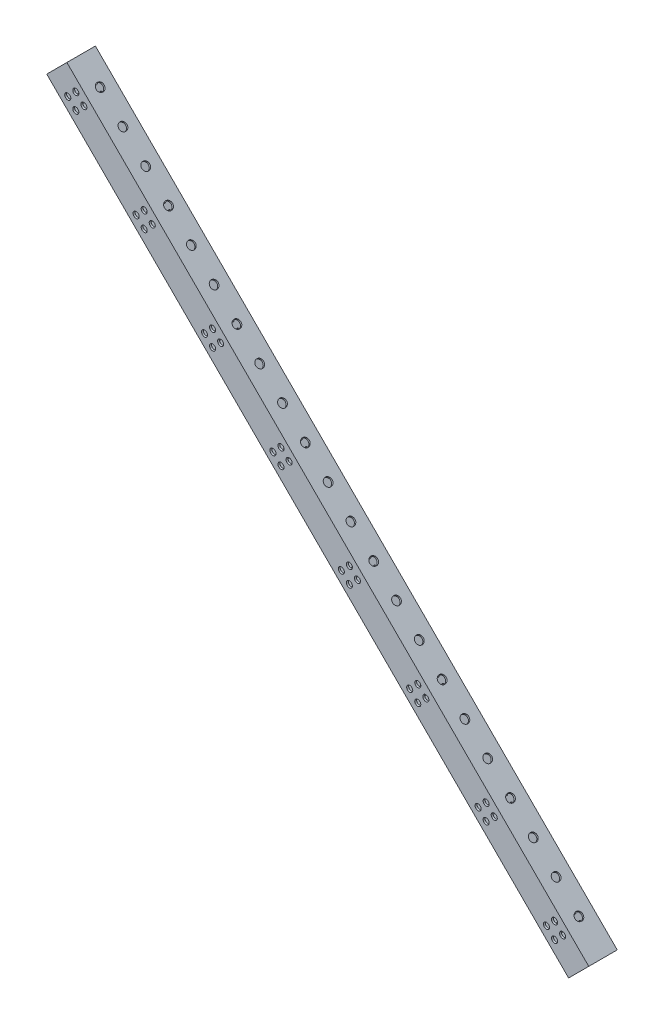
SolidWorks part; units mm, degrees
ref_plane "前视基准面" through (0, 0, 0) normal (0, 0, 1) x (1, 0, 0)
ref_plane "上视基准面" through (0, 0, 0) normal (0, 1, 0) x (1, 0, 0)
ref_plane "右视基准面" through (0, 0, 0) normal (1, 0, 0) x (0, 0, -1)
other "Configuration Table"
sketch "草图1" plane through (0, 0, 0) normal (0, 0, 1) x (1, 0, 0)
  line L0 (0, 560) -> (0, 0) construction
  line L1 (0, 0) -> (560, 0) construction
  line L2 (0, 0) -> (49.7921, 0) construction
  line L3 (5.3033, 565.3033) -> (-5.3033, 554.6967)
  line L8 (-5.3033, 554.6967) -> (554.6967, -5.3033)
  line L9 (554.6967, -5.3033) -> (565.3033, 5.3033)
  line L10 (565.3033, 5.3033) -> (5.3033, 565.3033)
  point P5 (0, 0)
  dimension "D1" = 90
  dimension "D2" = 560
  dimension "D3" = 560
  dimension "D4" = 15
extrude "凸台-拉伸1" add sketch "草图1" along normal blind 15
sketch "草图3" plane through (-280, 280, 0) normal (-0.7071, 0.7071, 0) x (0, 0, 1)
  line L0 (15, 403.4798) -> (0, 403.4798) construction
  line L1 (1, 389.4798) -> (14, 389.4798)
  line L2 (1, 389.4798) -> (1, 402.4798)
  line L3 (1, 402.4798) -> (14, 402.4798)
  line L4 (14, 389.4798) -> (14, 402.4798)
  line L5 (0, 403.4798) -> (0, 388.4798) construction
  dimension "D1" = 1
  dimension "D2" = 1
  dimension "D3" = 13
extrude "切除-拉伸2" cut sketch "草图3" against normal up to surface (791.9596 mm away) up to face at (560, 0, 7.5)
sketch "草图4" plane through (0, 0, 15) normal (0, 0, 1) x (1, 0, 0)
  line L0 (0, 560) -> (9.2347, 550.7653) construction
  line L2 (5.3033, 565.3033) -> (-5.3033, 554.6967) construction
  line L3 (-5.3033, 554.6967) -> (554.6967, -5.3033) construction
  line L4 (0, 560) -> (0, 540) construction
  line L5 (0, 540) -> (20, 540) construction
  circle A0 centre (5.7574, 550) radius 1.6
  circle A1 centre (10, 554.2426) radius 1.6
  circle A2 centre (10, 545.7574) radius 1.6
  circle A3 centre (14.2426, 550) radius 1.6
  circle A4 centre (41.7574, 514) radius 1.6
  circle A5 centre (46, 518.2426) radius 1.6
  circle A6 centre (50.2426, 514) radius 1.6
  circle A7 centre (46, 509.7574) radius 1.6
  circle A8 centre (77.7574, 478) radius 1.6
  circle A9 centre (82, 482.2426) radius 1.6
  circle A10 centre (86.2426, 478) radius 1.6
  circle A11 centre (82, 473.7574) radius 1.6
  circle A12 centre (113.7574, 442) radius 1.6
  circle A13 centre (118, 446.2426) radius 1.6
  circle A14 centre (122.2426, 442) radius 1.6
  circle A15 centre (118, 437.7574) radius 1.6
  circle A16 centre (149.7574, 406) radius 1.6
  circle A17 centre (154, 410.2426) radius 1.6
  circle A18 centre (158.2426, 406) radius 1.6
  circle A19 centre (154, 401.7574) radius 1.6
  circle A20 centre (185.7574, 370) radius 1.6
  circle A21 centre (190, 374.2426) radius 1.6
  circle A22 centre (194.2426, 370) radius 1.6
  circle A23 centre (190, 365.7574) radius 1.6
  circle A24 centre (221.7574, 334) radius 1.6
  circle A25 centre (226, 338.2426) radius 1.6
  circle A26 centre (230.2426, 334) radius 1.6
  circle A27 centre (226, 329.7574) radius 1.6
  circle A28 centre (257.7574, 298) radius 1.6
  circle A29 centre (262, 302.2426) radius 1.6
  circle A30 centre (266.2426, 298) radius 1.6
  circle A31 centre (262, 293.7574) radius 1.6
  circle A32 centre (293.7574, 262) radius 1.6
  circle A33 centre (298, 266.2426) radius 1.6
  circle A34 centre (302.2426, 262) radius 1.6
  circle A35 centre (298, 257.7574) radius 1.6
  circle A36 centre (329.7574, 226) radius 1.6
  circle A37 centre (334, 230.2426) radius 1.6
  circle A38 centre (338.2426, 226) radius 1.6
  circle A39 centre (334, 221.7574) radius 1.6
  circle A40 centre (365.7574, 190) radius 1.6
  circle A41 centre (370, 194.2426) radius 1.6
  circle A42 centre (374.2426, 190) radius 1.6
  circle A43 centre (370, 185.7574) radius 1.6
  circle A44 centre (401.7574, 154) radius 1.6
  circle A45 centre (406, 158.2426) radius 1.6
  circle A46 centre (410.2426, 154) radius 1.6
  circle A47 centre (406, 149.7574) radius 1.6
  circle A48 centre (437.7574, 118) radius 1.6
  circle A49 centre (442, 122.2426) radius 1.6
  circle A50 centre (446.2426, 118) radius 1.6
  circle A51 centre (442, 113.7574) radius 1.6
  circle A52 centre (473.7574, 82) radius 1.6
  circle A53 centre (478, 86.2426) radius 1.6
  circle A54 centre (482.2426, 82) radius 1.6
  circle A55 centre (478, 77.7574) radius 1.6
  circle A56 centre (509.7574, 46) radius 1.6
  circle A57 centre (514, 50.2426) radius 1.6
  circle A58 centre (518.2426, 46) radius 1.6
  circle A59 centre (514, 41.7574) radius 1.6
  circle A60 centre (545.7574, 10) radius 1.6
  circle A61 centre (550, 14.2426) radius 1.6
  circle A62 centre (554.2426, 10) radius 1.6
  circle A63 centre (550, 5.7574) radius 1.6
  dimension "D7" = 3.2
  dimension "D1" = 7.5
  dimension "D2" = 20
  dimension "D3" = 6
  dimension "D4" = 6
  dimension "D5" = 6
  dimension "D6" = 10
  dimension "D8" = 16
extrude "切除-拉伸3" cut sketch "草图4" against normal up to surface (15 mm away) up to face at (280, 280, 0)
sketch "草图5" plane through (274.6967, 274.6967, 0) normal (-0.7071, -0.7071, 0) x (0, 0, 1)
  line L0 (7.5, 395.9798) -> (7.5, 398.6945) construction
  line L2 (0, 395.9798) -> (0, -395.9798) construction
  line L3 (15, 395.9798) -> (0, 395.9798) construction
  circle A0 centre (7.5, 381.8377) radius 2.1
  circle A1 centre (7.5, 364.8671) radius 2.1
  circle A2 centre (7.5, 347.8965) radius 2.1
  circle A3 centre (7.5, 330.926) radius 2.1
  circle A4 centre (7.5, 313.9554) radius 2.1
  circle A5 centre (7.5, 296.9848) radius 2.1
  circle A6 centre (7.5, 280.0143) radius 2.1
  circle A7 centre (7.5, 263.0437) radius 2.1
  circle A8 centre (7.5, 246.0732) radius 2.1
  circle A9 centre (7.5, 229.1026) radius 2.1
  circle A10 centre (7.5, 212.132) radius 2.1
  circle A11 centre (7.5, 195.1615) radius 2.1
  circle A12 centre (7.5, 178.1909) radius 2.1
  circle A13 centre (7.5, 161.2203) radius 2.1
  circle A14 centre (7.5, 144.2498) radius 2.1
  circle A15 centre (7.5, 127.2792) radius 2.1
  circle A16 centre (7.5, 110.3087) radius 2.1
  circle A17 centre (7.5, 93.3381) radius 2.1
  circle A18 centre (7.5, 76.3675) radius 2.1
  circle A19 centre (7.5, 59.397) radius 2.1
  circle A20 centre (7.5, 42.4264) radius 2.1
  circle A21 centre (7.5, 25.4558) radius 2.1
  dimension "D2" = 4.2
  dimension "D1" = 7.5
  dimension "D3" = 14.1421
  dimension "D4" = 22
extrude "切除-拉伸4" cut sketch "草图5" against normal up to surface (15 mm away) up to face at (285.3033, 285.3033, 7.5)
sketch "草图6" plane through (280, -280, 0) normal (0.7071, -0.7071, 0) x (0, 0, -1)
  line L1 (-15, 403.4798) -> (0, 403.4798)
  line L2 (-15, 403.4798) -> (-15, 388.4798)
  line L3 (-15, 388.4798) -> (0, 388.4798)
  line L4 (0, 403.4798) -> (0, 388.4798)
extrude "切除-拉伸5" cut sketch "草图6" against normal blind 403.4798
